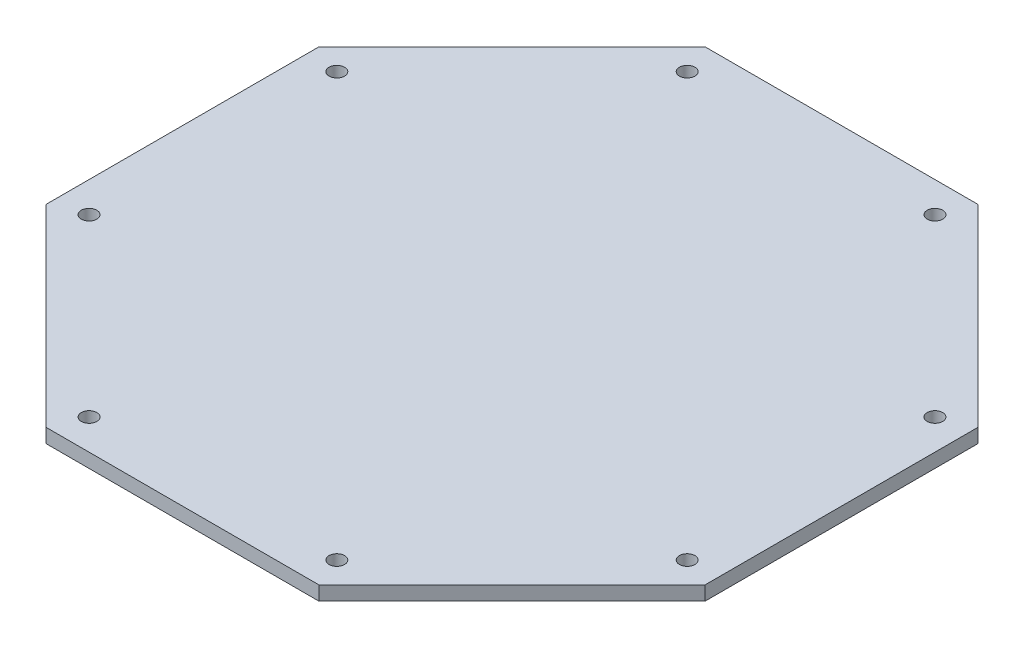
SolidWorks part; units mm, degrees
ref_plane "Plano frontal" through (0, 0, 0) normal (0, 0, 1) x (1, 0, 0)
ref_plane "Plano superior" through (0, 0, 0) normal (0, 1, 0) x (1, 0, 0)
ref_plane "Plano direito" through (0, 0, 0) normal (1, 0, 0) x (0, 0, -1)
sketch "Esboço1" plane through (0, 0, 0) normal (0, 1, 0) x (1, 0, 0)
  line L1 (70, 28.9949) -> (28.9949, 70)
  line L2 (28.9949, 70) -> (-28.9949, 70)
  line L3 (-28.9949, 70) -> (-70, 28.9949)
  line L4 (-70, 28.9949) -> (-70, -28.9949)
  line L5 (-70, -28.9949) -> (-28.9949, -70)
  line L6 (-28.9949, -70) -> (28.9949, -70)
  line L7 (28.9949, -70) -> (70, -28.9949)
  line L8 (70, -28.9949) -> (70, 28.9949)
  circle A0 centre (0, 0) radius 70 construction
  point P13 (70, 0)
  dimension "D1" = 140
extrude "Ressalto-extrusão1" add sketch "Esboço1" along normal mid plane 3
sketch "Esboço2" plane through (0, -1.5, 0) normal (0, -1, 0) x (1, 0, 0)
  line L0 (-28.9949, 70) -> (-26.3162, 63.5328) construction
  line L1 (-28.9949, 70) -> (28.9949, 70) construction
  line L2 (26.3162, 63.5328) -> (28.9949, 70) construction
  line L3 (63.5328, 26.3162) -> (70, 28.9949) construction
  line L4 (63.5328, -26.3162) -> (70, -28.9949) construction
  line L5 (70, 28.9949) -> (70, -28.9949) construction
  line L6 (26.3162, -63.5328) -> (28.9949, -70) construction
  line L7 (-28.9949, -70) -> (-26.3162, -63.5328) construction
  line L8 (-70, 28.9949) -> (-63.5328, 26.3162) construction
  line L9 (-70, -28.9949) -> (-63.5328, -26.3162) construction
  line L10 (28.9949, 70) -> (70, 28.9949) construction
  line L11 (70, -28.9949) -> (28.9949, -70) construction
  line L12 (28.9949, -70) -> (-28.9949, -70) construction
  line L13 (-70, -28.9949) -> (-70, 28.9949) construction
  line L14 (-28.9949, -70) -> (-70, -28.9949) construction
  circle A0 centre (-26.3162, 63.5328) radius 1.65
  circle A1 centre (26.3162, 63.5328) radius 1.65
  circle A2 centre (63.5328, 26.3162) radius 1.65
  circle A3 centre (63.5328, -26.3162) radius 1.65
  circle A4 centre (26.3162, -63.5328) radius 1.65
  circle A5 centre (-26.3162, -63.5328) radius 1.65
  circle A6 centre (-63.5328, 26.3162) radius 1.65
  circle A7 centre (-63.5328, -26.3162) radius 1.65
  dimension "D3" = 3.3
  dimension "D1" = 67.5
  dimension "D2" = 7
  dimension "D4" = 67.5
  dimension "D5" = 67.5
  dimension "D6" = 67.5
  dimension "D7" = 67.5
  dimension "D8" = 67.5
  dimension "D9" = 67.5
  dimension "D10" = 67.5
extrude "Corte-extrusão1" cut sketch "Esboço2" against normal through all
